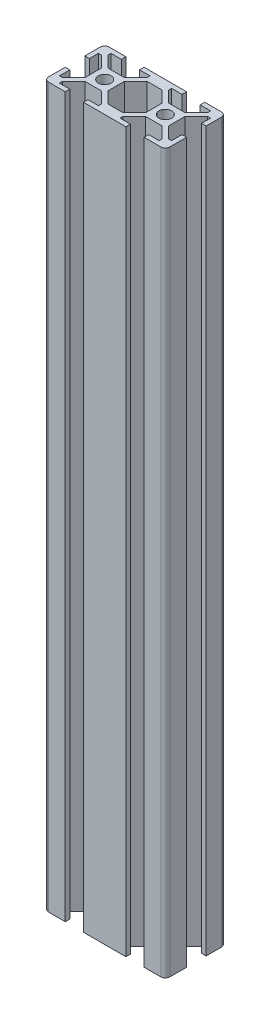
SolidWorks part; units mm, degrees
material "6063-O, Extruded Rod (SS)"
ref_plane "Front Plane" through (0, 0, 0) normal (0, 0, 1) x (1, 0, 0)
ref_plane "Top Plane" through (0, 0, 0) normal (0, 1, 0) x (1, 0, 0)
ref_plane "Right Plane" through (0, 0, 0) normal (1, 0, 0) x (0, 0, -1)
sketch "Sketch1" plane through (0, 0, 0) normal (0, 1, 0) x (1, 0, 0)
  line L0 (0, 0) -> (7, 0)
  line L1 (0, 0) -> (40, 0) construction
  line L2 (0, 0) -> (0, 20) construction
  line L3 (0, 20) -> (40, 20) construction
  line L4 (40, 0) -> (40, 20) construction
  line L5 (7, 0) -> (7, 1.5)
  line L6 (7, 1.5) -> (3.5607, 1.5)
  line L7 (3.5607, 1.5) -> (3.5607, 2.5)
  line L8 (3.5607, 2.5) -> (7.2607, 6.2)
  line L9 (12.7393, 6.2) -> (16.4393, 2.5)
  line L10 (16.4393, 2.5) -> (16.4393, 1.5)
  line L11 (13, 1.5) -> (13, 0)
  line L12 (13, 0) -> (27, 0)
  line L13 (27, 0) -> (27, 1.5)
  line L14 (27, 1.5) -> (23.5607, 1.5)
  line L15 (23.5607, 1.5) -> (23.5607, 2.5)
  line L16 (23.5607, 2.5) -> (27.2607, 6.2)
  line L17 (36.4393, 2.5) -> (36.4393, 1.5)
  line L18 (36.4393, 1.5) -> (33, 1.5)
  line L19 (33, 1.5) -> (33, 0)
  line L20 (33, 0) -> (40, 0)
  line L21 (40, 0) -> (40, 7)
  line L22 (40, 7) -> (38.5, 7)
  line L23 (38.5, 7) -> (38.5, 3.5607)
  line L24 (38.5, 3.5607) -> (37.5, 3.5607)
  line L25 (37.5, 3.5607) -> (33.8, 7.2607)
  line L26 (33.8, 7.2607) -> (33.8, 12.7393)
  line L27 (33.8, 12.7393) -> (37.5, 16.4393)
  line L28 (37.5, 16.4393) -> (38.5, 16.4393)
  line L29 (38.5, 16.4393) -> (38.5, 13.4532)
  line L30 (38.5, 13.4532) -> (40, 13.4532)
  line L31 (40, 13.4532) -> (40, 20)
  line L32 (40, 20) -> (33, 20)
  line L33 (33, 20) -> (33, 18.5)
  line L34 (33, 18.5) -> (36.4393, 18.5)
  line L35 (36.4393, 18.5) -> (36.4393, 17.5)
  line L36 (36.4393, 17.5) -> (32.7393, 13.8)
  line L37 (32.7393, 13.8) -> (27.2607, 13.8)
  line L38 (27.2607, 13.8) -> (23.5607, 17.5)
  line L39 (23.5607, 17.5) -> (23.5607, 18.5)
  line L40 (23.5607, 18.5) -> (27, 18.5)
  line L41 (27, 18.5) -> (27, 20)
  line L42 (27, 20) -> (13, 20)
  line L43 (13, 20) -> (13, 18.5)
  line L44 (13, 18.5) -> (16.4393, 18.5)
  line L45 (16.4393, 18.5) -> (16.4393, 17.5)
  line L46 (16.4393, 17.5) -> (12.7393, 13.8)
  line L47 (12.7393, 13.8) -> (7.2607, 13.8)
  line L48 (7.2607, 13.8) -> (3.5607, 17.5)
  line L49 (3.5607, 17.5) -> (3.5607, 18.5)
  line L50 (3.5607, 18.5) -> (7, 18.5)
  line L51 (7, 18.5) -> (7, 20)
  line L52 (7, 20) -> (0, 20)
  line L53 (0, 20) -> (0, 13.4532)
  line L54 (0, 13.4532) -> (1.5, 13.4532)
  line L55 (1.5, 13.4532) -> (1.5, 16.4393)
  line L56 (7.2607, 6.2) -> (12.7393, 6.2)
  line L57 (27.2607, 6.2) -> (32.7393, 6.2)
  line L58 (16.4393, 1.5) -> (13, 1.5)
  line L59 (32.7393, 6.2) -> (36.4393, 2.5)
  line L60 (40, 10) -> (-12.444, 10) construction
  line L61 (20, -12.9166) -> (20, 20) construction
  line L62 (1.5, 16.4393) -> (2.5, 16.4393)
  line L63 (2.5, 16.4393) -> (6.2, 12.7393)
  line L64 (6.2, 12.7393) -> (6.2, 7.2607)
  line L65 (6.2, 7.2607) -> (2.5, 3.5607)
  line L66 (2.5, 3.5607) -> (1.5, 3.5607)
  line L67 (1.5, 3.5607) -> (1.5, 7)
  line L68 (1.5, 7) -> (0, 7)
  line L69 (0, 7) -> (0, 0)
  line L70 (17.497, 16.4583) -> (13.778, 12.7393)
  line L71 (13.778, 12.7393) -> (13.778, 7.2607)
  line L72 (13.778, 7.2607) -> (17.497, 3.5417)
  line L73 (17.497, 3.5417) -> (22.503, 3.5417)
  line L74 (22.503, 3.5417) -> (26.222, 7.2607)
  line L75 (26.222, 7.2607) -> (26.222, 12.7393)
  line L76 (26.222, 12.7393) -> (22.503, 16.4583)
  line L77 (22.503, 16.4583) -> (17.497, 16.4583)
  circle A0 centre (10, 10) radius 2.1
  circle A1 centre (30, 10) radius 2.1
  point P22 (33.8, 10)
  point P34 (30, 6.2)
  point P66 (10, 6.2)
  point P79 (20, 3.5417)
  point P85 (13.778, 10)
  dimension "D6" = 4.2
  dimension "D1" = 40
  dimension "D2" = 20
  dimension "D3" = 6
  dimension "D4" = 1.5
  dimension "D5" = 6.2
  dimension "D7" = 20
  dimension "D8" = 1.5
  dimension "D9" = 1
  dimension "D10" = 45
extrude "Boss-Extrude1" add sketch "Sketch1" along normal blind 237
fillet "Fillet1" radius 1.5 4 edges at (0, 118.5, 0) (0, 118.5, -20) (40, 118.5, 0) (40, 118.5, -20)
